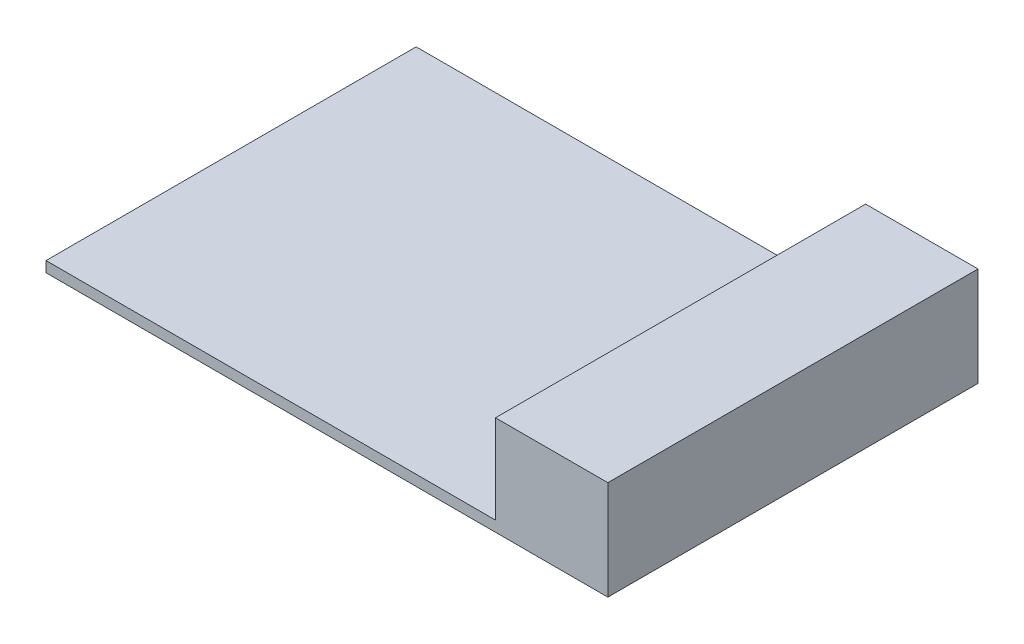
SolidWorks part; units mm, degrees
ref_plane "Front Plane" through (0, 0, 0) normal (0, 0, 1) x (1, 0, 0)
ref_plane "Top Plane" through (0, 0, 0) normal (0, 1, 0) x (1, 0, 0)
ref_plane "Right Plane" through (0, 0, 0) normal (1, 0, 0) x (0, 0, -1)
sketch "Sketch1" plane through (0, 0, 0) normal (0, 1, 0) x (1, 0, 0)
  line L0 (-42.5, -28) -> (42.5, -28)
  line L1 (42.5, -28) -> (42.5, 28)
  line L2 (42.5, 28) -> (-42.5, 28)
  line L3 (-42.5, 28) -> (-42.5, -28)
extrude "Boss-Extrude1" add sketch "Sketch1" along normal blind 1.6
sketch "Sketch2" plane through (0, 0, 0) normal (0, 1, 0) x (1, 0, 0)
  line L0 (25.5, -28) -> (42.5, -28)
  line L1 (42.5, -28) -> (42.5, 28)
  line L2 (42.5, 28) -> (25.5, 28)
  line L3 (25.5, 28) -> (25.5, -28)
extrude "Boss-Extrude2" add sketch "Sketch2" along normal blind 15
sketch "Sketch3" plane through (0, 0, 0) normal (0, 1, 0) x (1, 0, 0)
  circle A0 centre (29, 24.5) radius 1.35
  circle A1 centre (29, -24.5) radius 1.35
  circle A2 centre (-29, 24.5) radius 1.35
  circle A3 centre (-29, -24.5) radius 1.35
